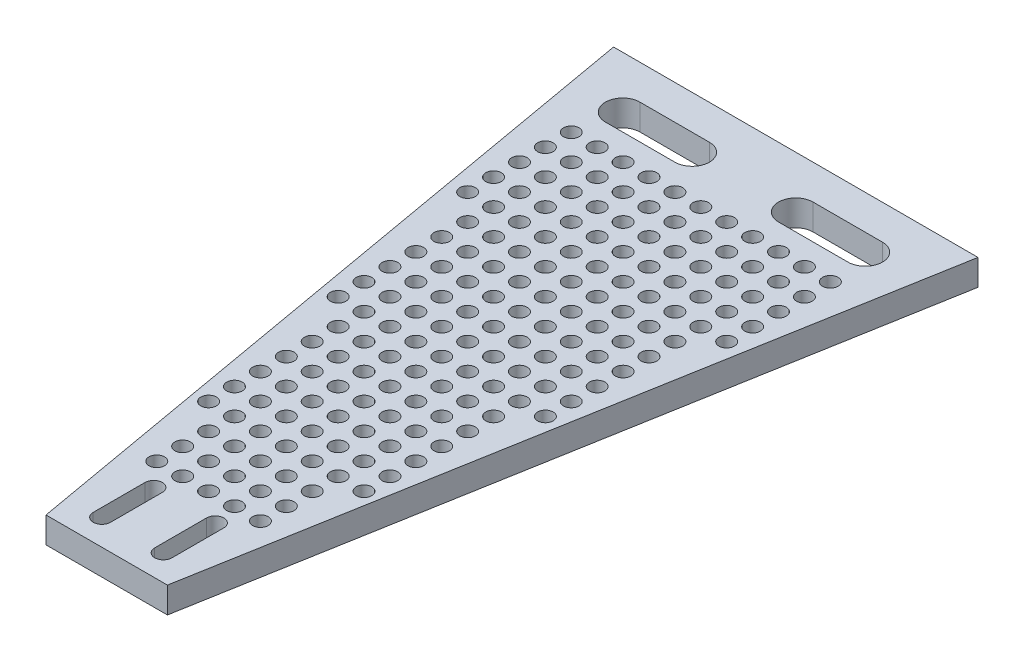
SolidWorks part; units mm, degrees
ref_plane "Front Plane" through (0, 0, 0) normal (0, 0, 1) x (1, 0, 0)
ref_plane "Top Plane" through (0, 0, 0) normal (0, 1, 0) x (1, 0, 0)
ref_plane "Right Plane" through (0, 0, 0) normal (1, 0, 0) x (0, 0, -1)
ref_plane "Plane1" through (0, 0, 0) normal (0, 1, 0) x (1, 0, 0)
sketch "Sketch1" plane through (0, 0, 0) normal (0, 1, 0) x (1, 0, 0)
  line L0 (105.5072, 199.4928) -> (35.1553, -199.4928)
  line L1 (-105.5072, -199.4928) -> (105.5072, -199.4928)
  line L2 (-105.5072, -199.4928) -> (-105.5072, 199.4928)
  line L3 (-105.5072, 199.4928) -> (105.5072, 199.4928)
  line L4 (105.5072, -199.4928) -> (105.5072, 199.4928)
  line L5 (-105.5072, -199.4928) -> (105.5072, 199.4928) construction
  line L6 (-105.5072, 199.4928) -> (105.5072, -199.4928) construction
  line L7 (-105.5072, 199.4928) -> (-35.1553, -199.4928)
  point P0 (0, 0)
extrude "Boss-Extrude1" add sketch "Sketch1" along normal blind 15 contours L3 L7 L1 L0
sketch "Sketch2" plane through (0, 0, 0) normal (0, -1, 0) x (-1, 0, 0)
  line L0 (0, 199.4928) -> (0, -199.4928)
  line L1 (105.5072, 199.4928) -> (-105.5072, 199.4928) construction
  line L2 (35.1553, -199.4928) -> (-35.1553, -199.4928) construction
  line L3 (100.2174, 169.4928) -> (-100.2174, 169.4928)
  line L4 (105.5072, 199.4928) -> (35.1553, -199.4928) construction
  line L5 (-105.5072, 199.4928) -> (-35.1553, -199.4928) construction
  line L6 (30, 199.4928) -> (30, 138.6373)
  line L7 (70.2174, 199.4928) -> (70.2174, 148.6373)
  line L8 (70.2174, 169.4928) -> (30, 169.4928) construction
  line L9 (70.2174, 159.4928) -> (30, 159.4928)
  line L10 (70.2174, 179.4928) -> (30, 179.4928)
  line L11 (-30, 199.4928) -> (-30, 140.8002)
  line L12 (-70.2174, 199.4928) -> (-70.2174, 140.8002)
  line L13 (-30, 169.4928) -> (-70.2174, 169.4928) construction
  line L14 (-30, 159.4928) -> (-70.2174, 159.4928)
  line L15 (-30, 179.4928) -> (-70.2174, 179.4928)
  line L16 (37.8002, -184.4928) -> (-37.8002, -184.4928)
  line L17 (-17.8002, -199.4928) -> (-17.8002, -131.7358)
  line L18 (17.8002, -199.4928) -> (17.8002, -131.7358)
  line L19 (-43.09, -154.4928) -> (43.09, -154.4928)
  line L20 (-17.8002, -154.4928) -> (-17.8002, -184.4928) construction
  line L21 (-12.8002, -154.4928) -> (-12.8002, -184.4928)
  line L22 (-22.8002, -154.4928) -> (-22.8002, -184.4928)
  line L23 (17.8002, -154.4928) -> (17.8002, -184.4928) construction
  line L24 (22.8002, -154.4928) -> (22.8002, -184.4928)
  line L25 (12.8002, -154.4928) -> (12.8002, -184.4928)
  arc A0 (70.2174, 159.4928) -> (70.2174, 179.4928) centre (70.2174, 169.4928) ccw
  arc A1 (30, 179.4928) -> (30, 159.4928) centre (30, 169.4928) ccw
  arc A2 (-30, 159.4928) -> (-30, 179.4928) centre (-30, 169.4928) ccw
  arc A3 (-70.2174, 179.4928) -> (-70.2174, 159.4928) centre (-70.2174, 169.4928) ccw
  arc A4 (-12.8002, -154.4928) -> (-22.8002, -154.4928) centre (-17.8002, -154.4928) ccw
  arc A5 (-22.8002, -184.4928) -> (-12.8002, -184.4928) centre (-17.8002, -184.4928) ccw
  arc A6 (22.8002, -154.4928) -> (12.8002, -154.4928) centre (17.8002, -154.4928) ccw
  arc A7 (12.8002, -184.4928) -> (22.8002, -184.4928) centre (17.8002, -184.4928) ccw
  point P16 (0, 0)
  point P19 (50.1087, 169.4928)
  point P30 (-50.1087, 169.4928)
  point P45 (-17.8002, -169.4928)
  point P50 (17.8002, -169.4928)
  dimension "D4" = 30
  dimension "D6" = 15
  dimension "D1" = 30
  dimension "D2" = 30
  dimension "D3" = 30
  dimension "D5" = 30
  dimension "D7" = 30
  dimension "D8" = 20
  dimension "D9" = 20
extrude "Cut-Extrude1" cut sketch "Sketch2" against normal blind 15 contours L15 A3 L14 A2 | L10 A1 L9 A0 | L22 A5 L21 A4 | L24 A7 L25 A6
sketch "Sketch3" plane through (0, 0, 0) normal (0, 1, 0) x (1, 0, 0)
  circle A0 centre (0, 144.4928) radius 4.5
  circle A1 centre (15, 144.4928) radius 4.5
  circle A2 centre (30, 144.4928) radius 4.5
  circle A3 centre (45, 144.4928) radius 4.5
  circle A4 centre (60, 144.4928) radius 4.5
  circle A5 centre (75, 144.4928) radius 4.5
  circle A6 centre (15, 129.4928) radius 4.5
  circle A7 centre (30, 129.4928) radius 4.5
  circle A8 centre (45, 129.4928) radius 4.5
  circle A9 centre (60, 129.4928) radius 4.5
  circle A10 centre (75, 129.4928) radius 4.5
  circle A11 centre (15, 114.4928) radius 4.5
  circle A12 centre (30, 114.4928) radius 4.5
  circle A13 centre (45, 114.4928) radius 4.5
  circle A14 centre (60, 114.4928) radius 4.5
  circle A15 centre (75, 114.4928) radius 4.5
  circle A16 centre (15, 99.4928) radius 4.5
  circle A17 centre (30, 99.4928) radius 4.5
  circle A18 centre (45, 99.4928) radius 4.5
  circle A19 centre (60, 99.4928) radius 4.5
  circle A20 centre (75, 99.4928) radius 4.5
  circle A21 centre (15, 84.4928) radius 4.5
  circle A22 centre (30, 84.4928) radius 4.5
  circle A23 centre (45, 84.4928) radius 4.5
  circle A24 centre (60, 84.4928) radius 4.5
  circle A25 centre (75, 84.4928) radius 4.5
  circle A26 centre (15, 69.4928) radius 4.5
  circle A27 centre (30, 69.4928) radius 4.5
  circle A28 centre (45, 69.4928) radius 4.5
  circle A29 centre (60, 69.4928) radius 4.5
  circle A31 centre (15, 54.4928) radius 4.5
  circle A32 centre (30, 54.4928) radius 4.5
  circle A33 centre (45, 54.4928) radius 4.5
  circle A34 centre (60, 54.4928) radius 4.5
  circle A36 centre (15, 39.4928) radius 4.5
  circle A37 centre (30, 39.4928) radius 4.5
  circle A38 centre (45, 39.4928) radius 4.5
  circle A39 centre (60, 39.4928) radius 4.5
  circle A41 centre (15, 24.4928) radius 4.5
  circle A42 centre (30, 24.4928) radius 4.5
  circle A43 centre (45, 24.4928) radius 4.5
  circle A44 centre (60, 24.4928) radius 4.5
  circle A46 centre (15, 9.4928) radius 4.5
  circle A47 centre (30, 9.4928) radius 4.5
  circle A48 centre (45, 9.4928) radius 4.5
  circle A49 centre (60, 9.4928) radius 4.5
  circle A51 centre (15, -5.5072) radius 4.5
  circle A52 centre (30, -5.5072) radius 4.5
  circle A53 centre (45, -5.5072) radius 4.5
  circle A54 centre (60, -5.5072) radius 4.5
  circle A56 centre (15, -20.5072) radius 4.5
  circle A57 centre (30, -20.5072) radius 4.5
  circle A58 centre (45, -20.5072) radius 4.5
  circle A61 centre (15, -35.5072) radius 4.5
  circle A62 centre (30, -35.5072) radius 4.5
  circle A63 centre (45, -35.5072) radius 4.5
  circle A66 centre (15, -50.5072) radius 4.5
  circle A67 centre (30, -50.5072) radius 4.5
  circle A68 centre (45, -50.5072) radius 4.5
  circle A71 centre (15, -65.5072) radius 4.5
  circle A72 centre (30, -65.5072) radius 4.5
  circle A73 centre (45, -65.5072) radius 4.5
  circle A76 centre (15, -80.5072) radius 4.5
  circle A77 centre (30, -80.5072) radius 4.5
  circle A78 centre (45, -80.5072) radius 4.5
  circle A81 centre (15, -95.5072) radius 4.5
  circle A82 centre (30, -95.5072) radius 4.5
  circle A83 centre (45, -95.5072) radius 4.5
  circle A86 centre (15, -110.5072) radius 4.5
  circle A87 centre (30, -110.5072) radius 4.5
  circle A91 centre (15, -125.5072) radius 4.5
  circle A92 centre (30, -125.5072) radius 4.5
  circle A96 centre (15, -140.5072) radius 4.5
  circle A97 centre (30, -140.5072) radius 4.5
  circle A101 centre (0, 129.4928) radius 4.5
  circle A102 centre (0, 114.4928) radius 4.5
  circle A103 centre (0, 99.4928) radius 4.5
  circle A104 centre (0, 84.4928) radius 4.5
  circle A105 centre (0, 69.4928) radius 4.5
  circle A106 centre (0, 54.4928) radius 4.5
  circle A107 centre (0, 39.4928) radius 4.5
  circle A108 centre (0, 24.4928) radius 4.5
  circle A109 centre (0, 9.4928) radius 4.5
  circle A110 centre (0, -5.5072) radius 4.5
  circle A111 centre (0, -20.5072) radius 4.5
  circle A112 centre (0, -35.5072) radius 4.5
  circle A113 centre (0, -50.5072) radius 4.5
  circle A114 centre (0, -65.5072) radius 4.5
  circle A115 centre (0, -80.5072) radius 4.5
  circle A116 centre (0, -95.5072) radius 4.5
  circle A117 centre (0, -110.5072) radius 4.5
  circle A118 centre (0, -125.5072) radius 4.5
  circle A119 centre (0, -140.5072) radius 4.5
  circle A120 centre (-15, 144.4928) radius 4.5
  circle A121 centre (-30, 144.4928) radius 4.5
  circle A122 centre (-45, 144.4928) radius 4.5
  circle A123 centre (-60, 144.4928) radius 4.5
  circle A124 centre (-75, 144.4928) radius 4.5
  circle A125 centre (-30, 129.4928) radius 4.5
  circle A126 centre (-45, 129.4928) radius 4.5
  circle A127 centre (-60, 129.4928) radius 4.5
  circle A128 centre (-75, 129.4928) radius 4.5
  circle A129 centre (-30, 114.4928) radius 4.5
  circle A130 centre (-45, 114.4928) radius 4.5
  circle A131 centre (-60, 114.4928) radius 4.5
  circle A132 centre (-75, 114.4928) radius 4.5
  circle A133 centre (-30, 99.4928) radius 4.5
  circle A134 centre (-45, 99.4928) radius 4.5
  circle A135 centre (-60, 99.4928) radius 4.5
  circle A136 centre (-75, 99.4928) radius 4.5
  circle A137 centre (-30, 84.4928) radius 4.5
  circle A138 centre (-45, 84.4928) radius 4.5
  circle A139 centre (-60, 84.4928) radius 4.5
  circle A140 centre (-75, 84.4928) radius 4.5
  circle A141 centre (-30, 69.4928) radius 4.5
  circle A142 centre (-45, 69.4928) radius 4.5
  circle A143 centre (-60, 69.4928) radius 4.5
  circle A145 centre (-30, 54.4928) radius 4.5
  circle A146 centre (-45, 54.4928) radius 4.5
  circle A147 centre (-60, 54.4928) radius 4.5
  circle A149 centre (-30, 39.4928) radius 4.5
  circle A150 centre (-45, 39.4928) radius 4.5
  circle A151 centre (-60, 39.4928) radius 4.5
  circle A153 centre (-30, 24.4928) radius 4.5
  circle A154 centre (-45, 24.4928) radius 4.5
  circle A155 centre (-60, 24.4928) radius 4.5
  circle A157 centre (-30, 9.4928) radius 4.5
  circle A158 centre (-45, 9.4928) radius 4.5
  circle A159 centre (-60, 9.4928) radius 4.5
  circle A161 centre (-30, -5.5072) radius 4.5
  circle A162 centre (-45, -5.5072) radius 4.5
  circle A163 centre (-60, -5.5072) radius 4.5
  circle A165 centre (-30, -20.5072) radius 4.5
  circle A166 centre (-45, -20.5072) radius 4.5
  circle A169 centre (-30, -35.5072) radius 4.5
  circle A170 centre (-45, -35.5072) radius 4.5
  circle A173 centre (-30, -50.5072) radius 4.5
  circle A174 centre (-45, -50.5072) radius 4.5
  circle A177 centre (-30, -65.5072) radius 4.5
  circle A178 centre (-45, -65.5072) radius 4.5
  circle A181 centre (-30, -80.5072) radius 4.5
  circle A182 centre (-45, -80.5072) radius 4.5
  circle A185 centre (-30, -95.5072) radius 4.5
  circle A186 centre (-45, -95.5072) radius 4.5
  circle A189 centre (-30, -110.5072) radius 4.5
  circle A193 centre (-30, -125.5072) radius 4.5
  circle A197 centre (-30, -140.5072) radius 4.5
  circle A201 centre (-15, 129.4928) radius 4.5
  circle A202 centre (-15, 114.4928) radius 4.5
  circle A203 centre (-15, 99.4928) radius 4.5
  circle A204 centre (-15, 84.4928) radius 4.5
  circle A205 centre (-15, 69.4928) radius 4.5
  circle A206 centre (-15, 54.4928) radius 4.5
  circle A207 centre (-15, 39.4928) radius 4.5
  circle A208 centre (-15, 24.4928) radius 4.5
  circle A209 centre (-15, 9.4928) radius 4.5
  circle A210 centre (-15, -5.5072) radius 4.5
  circle A211 centre (-15, -20.5072) radius 4.5
  circle A212 centre (-15, -35.5072) radius 4.5
  circle A213 centre (-15, -50.5072) radius 4.5
  circle A214 centre (-15, -65.5072) radius 4.5
  circle A215 centre (-15, -80.5072) radius 4.5
  circle A216 centre (-15, -95.5072) radius 4.5
  circle A217 centre (-15, -110.5072) radius 4.5
  circle A218 centre (-15, -125.5072) radius 4.5
  circle A219 centre (-15, -140.5072) radius 4.5
  circle A220 centre (-75, 69.4928) radius 4.5 [skipped]
  circle A221 centre (-75, 54.4928) radius 4.5 [skipped]
  circle A222 centre (-75, 39.4928) radius 4.5 [skipped]
  circle A223 centre (-75, 24.4928) radius 4.5 [skipped]
  circle A224 centre (-75, 9.4928) radius 4.5 [skipped]
  circle A225 centre (-75, -5.5072) radius 4.5 [skipped]
  circle A226 centre (-75, -20.5072) radius 4.5 [skipped]
  circle A227 centre (-75, -35.5072) radius 4.5 [skipped]
  circle A228 centre (-75, -50.5072) radius 4.5 [skipped]
  circle A229 centre (-75, -65.5072) radius 4.5 [skipped]
  circle A230 centre (-75, -80.5072) radius 4.5 [skipped]
  circle A231 centre (-75, -95.5072) radius 4.5 [skipped]
  circle A232 centre (-60, -20.5072) radius 4.5 [skipped]
  circle A233 centre (-60, -35.5072) radius 4.5 [skipped]
  circle A234 centre (-60, -50.5072) radius 4.5 [skipped]
  circle A235 centre (-60, -65.5072) radius 4.5 [skipped]
  circle A236 centre (-60, -80.5072) radius 4.5 [skipped]
  circle A237 centre (-60, -95.5072) radius 4.5 [skipped]
  circle A238 centre (-60, -110.5072) radius 4.5 [skipped]
  circle A239 centre (-75, -110.5072) radius 4.5 [skipped]
  circle A240 centre (-60, -125.5072) radius 4.5 [skipped]
  circle A241 centre (-75, -125.5072) radius 4.5 [skipped]
  circle A242 centre (-60, -140.5072) radius 4.5 [skipped]
  circle A243 centre (-75, -140.5072) radius 4.5 [skipped]
  circle A244 centre (-45, -110.5072) radius 4.5 [skipped]
  circle A245 centre (-45, -125.5072) radius 4.5 [skipped]
  circle A246 centre (-45, -140.5072) radius 4.5 [skipped]
  circle A247 centre (75, 69.4928) radius 4.5 [skipped]
  circle A248 centre (75, 54.4928) radius 4.5 [skipped]
  circle A249 centre (75, 39.4928) radius 4.5 [skipped]
  circle A250 centre (75, 24.4928) radius 4.5 [skipped]
  circle A251 centre (75, 9.4928) radius 4.5 [skipped]
  circle A252 centre (75, -5.5072) radius 4.5 [skipped]
  circle A253 centre (75, -20.5072) radius 4.5 [skipped]
  circle A254 centre (75, -35.5072) radius 4.5 [skipped]
  circle A255 centre (75, -50.5072) radius 4.5 [skipped]
  circle A256 centre (75, -65.5072) radius 4.5 [skipped]
  circle A257 centre (75, -80.5072) radius 4.5 [skipped]
  circle A258 centre (75, -95.5072) radius 4.5 [skipped]
  circle A259 centre (75, -110.5072) radius 4.5 [skipped]
  circle A260 centre (75, -125.5072) radius 4.5 [skipped]
  circle A261 centre (75, -140.5072) radius 4.5 [skipped]
  circle A262 centre (60, -20.5072) radius 4.5 [skipped]
  circle A263 centre (60, -35.5072) radius 4.5 [skipped]
  circle A264 centre (60, -50.5072) radius 4.5 [skipped]
  circle A265 centre (60, -65.5072) radius 4.5 [skipped]
  circle A266 centre (60, -80.5072) radius 4.5 [skipped]
  circle A267 centre (60, -95.5072) radius 4.5 [skipped]
  circle A268 centre (60, -110.5072) radius 4.5 [skipped]
  circle A269 centre (60, -125.5072) radius 4.5 [skipped]
  circle A270 centre (60, -140.5072) radius 4.5 [skipped]
  circle A271 centre (45, -110.5072) radius 4.5 [skipped]
  circle A272 centre (45, -125.5072) radius 4.5 [skipped]
  circle A273 centre (45, -140.5072) radius 4.5 [skipped]
  dimension "D2" = 2
  dimension "D5" = 6
  dimension "D6" = 20
  dimension "D3" = 5
  dimension "D4" = 20
extrude "Cut-Extrude19" cut sketch "Sketch3" along normal blind 15
